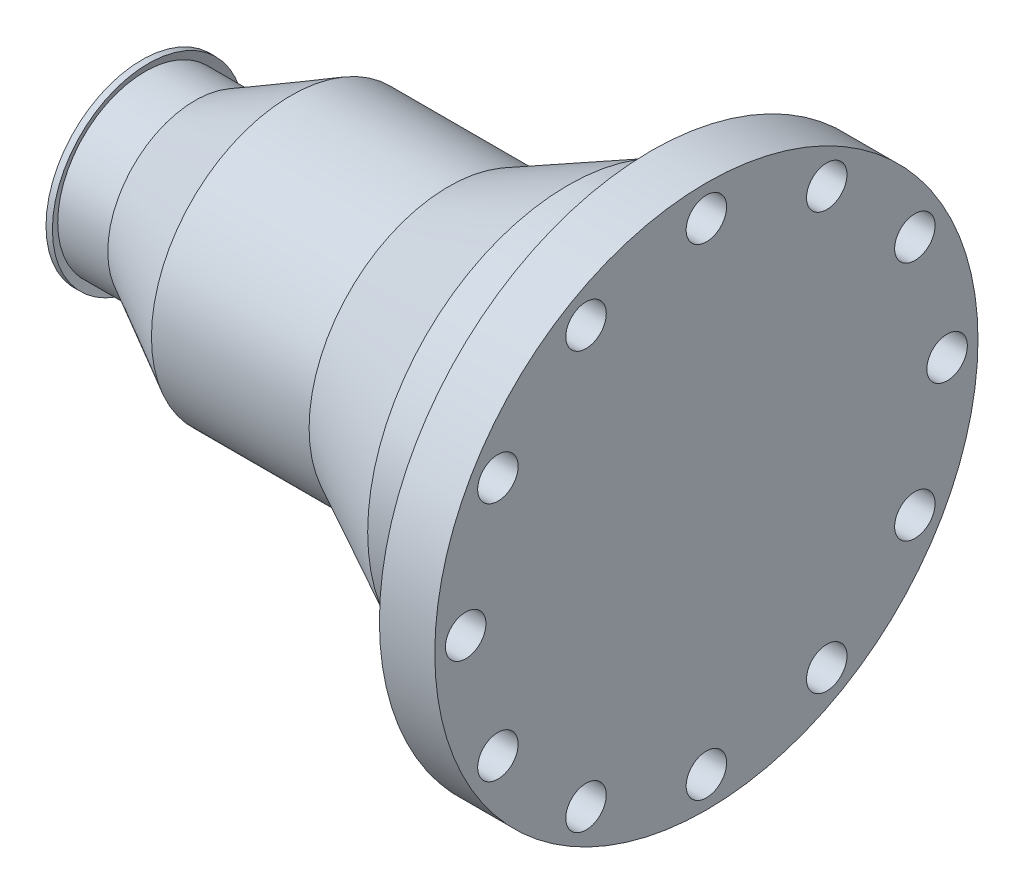
SolidWorks part; units mm, degrees
ref_plane "Спереди" through (0, 0, 0) normal (0, 0, 1) x (1, 0, 0)
ref_plane "Сверху" through (0, 0, 0) normal (0, 1, 0) x (1, 0, 0)
ref_plane "Справа" through (0, 0, 0) normal (1, 0, 0) x (0, 0, -1)
sketch "Эскиз1" plane through (0, 0, 0) normal (0, 0, 1) x (1, 0, 0)
  line L0 (0, 0) -> (265, 0)
  line L1 (0, 0) -> (0, 45)
  line L2 (0, 45) -> (3, 45)
  line L3 (3, 45) -> (1.5, 41)
  line L4 (1.5, 41) -> (25, 41)
  line L5 (25, 41) -> (70, 65.5)
  line L6 (70, 65.5) -> (144, 65.5)
  line L7 (144, 65.5) -> (200, 94)
  line L8 (200, 94) -> (220, 94)
  line L9 (220, 94) -> (220, 95)
  line L10 (220, 95) -> (239, 95)
  line L11 (239, 95) -> (239, 100)
  line L12 (239, 100) -> (239, 127.5)
  line L13 (239, 127.5) -> (265, 127.5)
  line L14 (265, 127.5) -> (265, 0)
revolve "Повернуть1" add sketch "Эскиз1" angle 360 about L0
sketch "Эскиз2" plane through (0, 0, 0) normal (0, 0, 1) x (1, 0, 0)
  line L0 (0, 0) -> (140, 0)
  line L1 (0, 0) -> (0, 31)
  line L2 (0, 45) -> (0, -45) construction
  line L3 (0, 31) -> (38, 31)
  line L4 (38, 31) -> (111.8808, 50.7963)
  line L5 (124.8206, 52.5839) -> (140, 52.5839)
  line L6 (140, 52.5839) -> (140, 0)
  arc A0 (111.8808, 50.7963) -> (124.8206, 52.5839) centre (125.4916, 0) cw
revolve "Вырез-Повернуть1" cut sketch "Эскиз2" angle 360 about L0
sketch "Эскиз3" plane through (0, 0, 0) normal (1, 0, 0) x (0, 0, -1)
  circle A0 centre (0, 113) radius 9.5
extrude "Вырез-Вытянуть1" cut sketch "Эскиз3" along normal through all
sketch "Эскиз4" plane through (0, 0, 0) normal (1, 0, 0) x (0, 0, -1)
  circle A0 centre (-56.5, 97.8609) radius 9.5
extrude "Вырез-Вытянуть2" cut sketch "Эскиз4" along normal through all
sketch "Эскиз5" plane through (0, 0, 0) normal (1, 0, 0) x (0, 0, -1)
  circle A0 centre (-97.8609, 56.5) radius 9.5
extrude "Вырез-Вытянуть3" cut sketch "Эскиз5" along normal through all
sketch "Эскиз6" plane through (0, 0, 0) normal (1, 0, 0) x (0, 0, -1)
  circle A0 centre (-113, 0) radius 9.5
extrude "Вырез-Вытянуть4" cut sketch "Эскиз6" along normal through all
sketch "Эскиз7" plane through (0, 0, 0) normal (1, 0, 0) x (0, 0, -1)
  circle A0 centre (-97.8609, -56.5) radius 9.5
extrude "Вырез-Вытянуть5" cut sketch "Эскиз7" along normal through all
sketch "Эскиз8" plane through (0, 0, 0) normal (1, 0, 0) x (0, 0, -1)
  circle A0 centre (-56.5, -97.8609) radius 9.5
extrude "Вырез-Вытянуть6" cut sketch "Эскиз8" along normal through all
sketch "Эскиз9" plane through (0, 0, 0) normal (1, 0, 0) x (0, 0, -1)
  circle A0 centre (0, -113) radius 9.5
extrude "Вырез-Вытянуть7" cut sketch "Эскиз9" along normal through all
sketch "Эскиз10" plane through (0, 0, 0) normal (1, 0, 0) x (0, 0, -1)
  circle A0 centre (56.5, -97.8609) radius 9.5
extrude "Вырез-Вытянуть8" cut sketch "Эскиз10" along normal through all
sketch "Эскиз11" plane through (0, 0, 0) normal (1, 0, 0) x (0, 0, -1)
  circle A0 centre (97.8609, -56.5) radius 9.5
extrude "Вырез-Вытянуть9" cut sketch "Эскиз11" along normal through all
sketch "Эскиз12" plane through (0, 0, 0) normal (1, 0, 0) x (0, 0, -1)
  circle A0 centre (113, 0) radius 9.5
extrude "Вырез-Вытянуть10" cut sketch "Эскиз12" along normal through all
sketch "Эскиз13" plane through (0, 0, 0) normal (1, 0, 0) x (0, 0, -1)
  circle A0 centre (97.8609, 56.5) radius 9.5
extrude "Вырез-Вытянуть11" cut sketch "Эскиз13" along normal through all
sketch "Эскиз14" plane through (0, 0, 0) normal (1, 0, 0) x (0, 0, -1)
  circle A0 centre (56.5, 97.8609) radius 9.5
extrude "Вырез-Вытянуть12" cut sketch "Эскиз14" along normal through all
